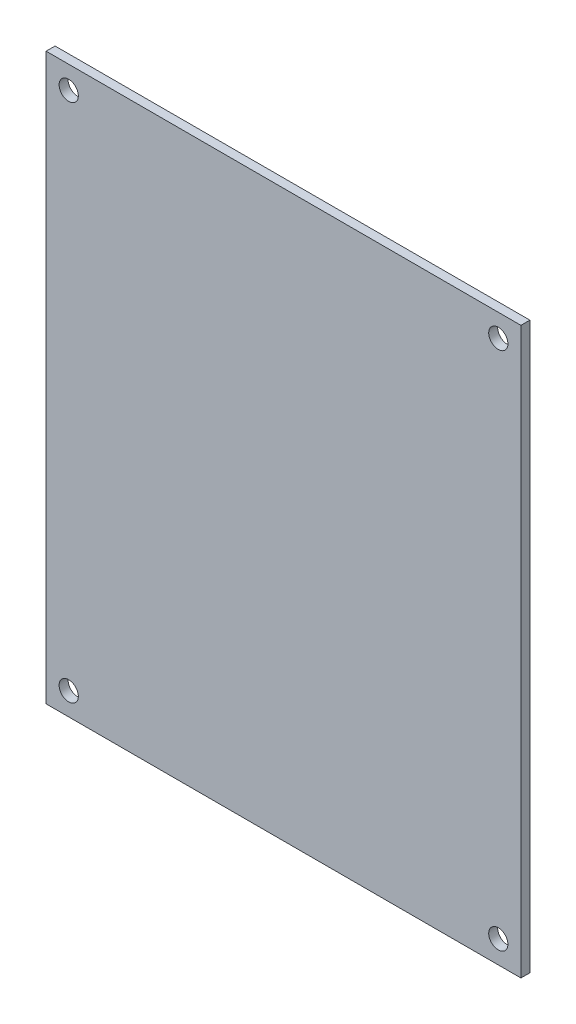
SolidWorks part; units mm, degrees
material "PBT General Purpose"
ref_plane "Front Plane" through (0, 0, 0) normal (0, 0, 1) x (1, 0, 0)
ref_plane "Top Plane" through (0, 0, 0) normal (0, 1, 0) x (1, 0, 0)
ref_plane "Right Plane" through (0, 0, 0) normal (1, 0, 0) x (0, 0, -1)
sketch "Sketch1" plane through (0, 0, 0) normal (1, 0, 0) x (0, 0, -1)
  line L1 (-0.7937, -50) -> (0.7937, -50)
  line L2 (-0.7937, -50) -> (-0.7937, 50)
  line L3 (-0.7937, 50) -> (0.7937, 50)
  line L4 (0.7937, -50) -> (0.7937, 50)
  line L5 (-0.7937, -50) -> (0.7937, 50) construction
  line L6 (-0.7937, 50) -> (0.7937, -50) construction
  point P0 (0, 0)
  dimension "D1" = 1.5875
  dimension "D2" = 100
extrude "Boss-Extrude1" add sketch "Sketch1" along normal mid plane 84
sketch "Sketch2" plane through (0, 0, 0.7937) normal (0, 0, 1) x (1, 0, 0)
  line L0 (-42, 50) -> (-42, -50) construction
  line L1 (42, 50) -> (-42, 50) construction
  line L2 (42, 50) -> (42, -50) construction
  line L3 (42, -50) -> (-42, -50) construction
  circle A0 centre (-38, 46) radius 1.7
  circle A1 centre (38, 46) radius 1.7
  circle A2 centre (38, -46) radius 1.7
  circle A3 centre (-38, -46) radius 1.7
  dimension "D1" = 3.4
  dimension "D2" = 4
  dimension "D3" = 4
  dimension "D4" = 4
  dimension "D5" = 4
extrude "Cut-Extrude1" cut sketch "Sketch2" against normal through all
equation "\"D2@Sketch1\"=100mm"
equation "\"D1@Boss-Extrude1\"=84mm"
equation "\"D1@Sketch2\"=3.4mm"
equation "\"D2@Sketch2\"=4mm"
equation "\"D3@Sketch2\"=4mm"
equation "\"D4@Sketch2\"=\"D2@Sketch2\""
equation "\"D5@Sketch2\"=\"D3@Sketch2\""
